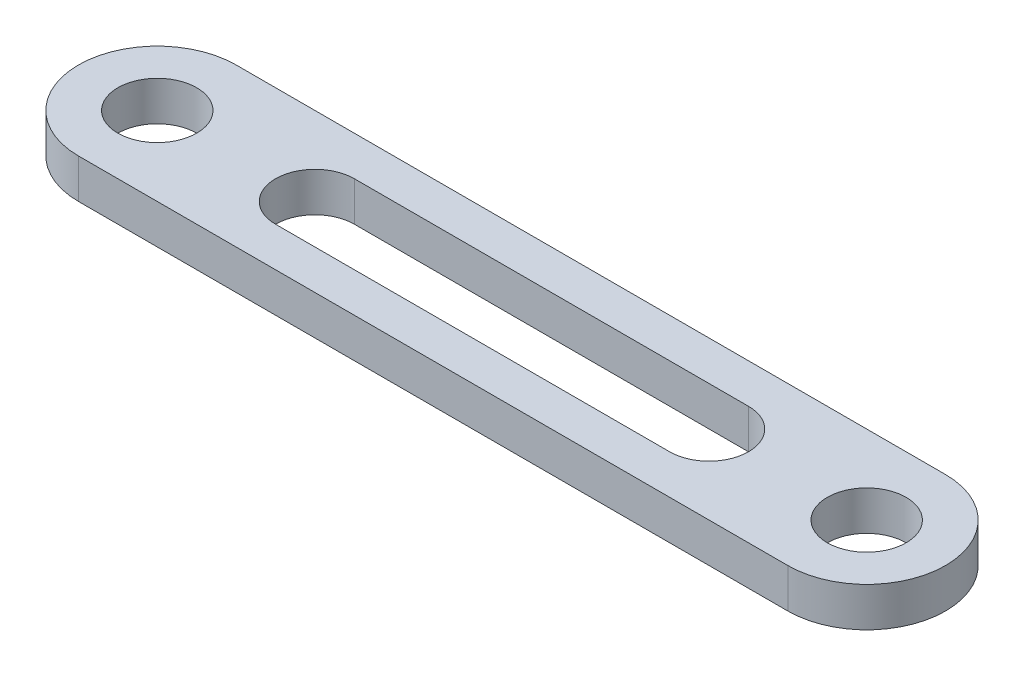
SolidWorks part; units mm, degrees
ref_plane "Front Plane" through (0, 0, 0) normal (0, 0, 1) x (1, 0, 0)
ref_plane "Top Plane" through (0, 0, 0) normal (0, 1, 0) x (1, 0, 0)
ref_plane "Right Plane" through (0, 0, 0) normal (1, 0, 0) x (0, 0, -1)
sketch "Sketch1" plane through (0, 0, 0) normal (0, 1, 0) x (1, 0, 0)
  line L2 (-45, 10) -> (45, 10)
  line L3 (-45, -10) -> (45, -10)
  arc A0 (-45, 10) -> (-45, -10) centre (-45, 0) ccw
  arc A1 (45, -10) -> (45, 10) centre (45, 0) ccw
extrude "Boss-Extrude1" add sketch "Sketch1" along normal blind 5
sketch "Sketch2" plane through (0, 5, 0) normal (0, 1, 0) x (1, 0, 0)
  line L2 (-25, 5) -> (25, 5)
  line L3 (-25, -5) -> (25, -5)
  arc A2 (-25, 5) -> (-25, -5) centre (-25, 0) ccw
  arc A3 (25, -5) -> (25, 5) centre (25, 0) ccw
extrude "Cut-Extrude1" cut sketch "Sketch2" against normal through all
sketch "Sketch3" plane through (0, 5, 0) normal (0, 1, 0) x (1, 0, 0)
  circle A0 centre (45, 0) radius 5
extrude "Cut-Extrude2" cut sketch "Sketch3" against normal through all
sketch "Sketch4" plane through (0, 5, 0) normal (0, 1, 0) x (1, 0, 0)
  circle A0 centre (-45, 0) radius 5
extrude "Cut-Extrude3" cut sketch "Sketch4" against normal through all
